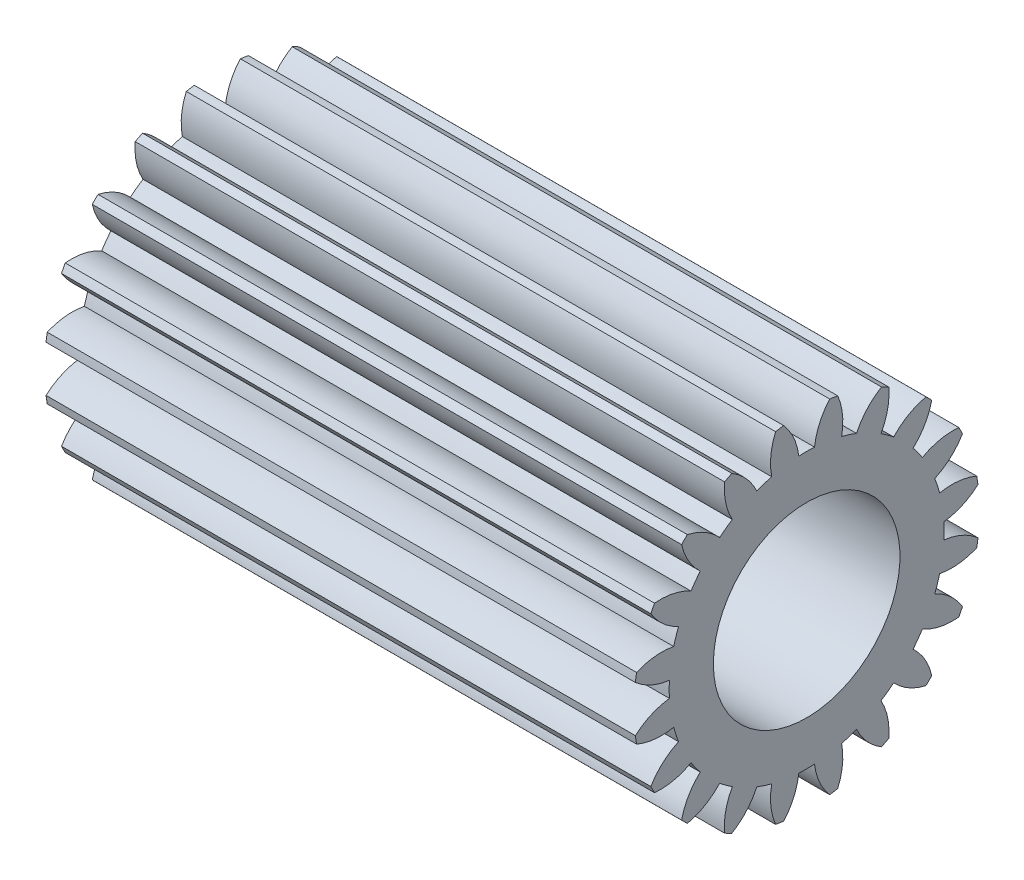
SolidWorks part; units mm, degrees
ref_plane "Plane1" through (0, 0, 0) normal (0, 0, 1) x (1, 0, 0)
ref_plane "Plane2" through (0, 0, 0) normal (0, 1, 0) x (1, 0, 0)
ref_plane "Plane3" through (0, 0, 0) normal (1, 0, 0) x (0, 0, -1)
sketch "HoldingSke" plane through (0, 0, 0) normal (0, 1, 0) x (1, 0, 0)
  line L0 (0, 0) -> (2.3492, -0.8551)
  line L1 (-15, 0) -> (100, 0) construction
  line L2 (0, 0) -> (-2.1039, 2.3779)
  line L3 (0, 0) -> (-11.863, 4.5341)
  line L4 (0, 0) -> (8.1152, 2.9537)
  line L5 (0, 0) -> (-46.8476, -17.4728)
  line L6 (0, 0) -> (-12.4344, -8.3896)
  line L7 (-2.1039, 2.3779) -> (8.6586, 51.2059)
  line L8 (-76.2, 54.61) -> (-75.9, 54.61)
  line L9 (-71.009, 38.7566) -> (-53.1078, 45.2721)
  line L10 (-76.2, 71.12) -> (104.1128, 71.12)
  line L11 (0, 0) -> (-15, 0)
  line L12 (-76.2, 101.6) -> (-76.185, 101.6)
  line L13 (24.9733, 27.94) -> (52.9518, 28.4284)
  line L14 (24.9733, 27.94) -> (24.9743, 27.94)
  line L15 (24.9733, 27.94) -> (100.4006, 29.5858)
  line L16 (-63.627, -0.4) -> (-12.827, -0.4)
  circle A0 centre (0, 0) radius 1
  circle A1 centre (0, 0) radius 3.499
  circle A2 centre (0, 0) radius 37.5
  circle A3 centre (0, 0) radius 2.375
  dimension "MHD" = 6.998
  dimension "Hub_dia" = 75
  dimension "Bore" = 2
  dimension "MBD" = 4.75
  dimension "Num_teeth" = 20
  dimension "Pitch" = 2.5
  dimension "Overall_len" = 50
  dimension "Show_teeth" = 20
  dimension "Thickness" = 15
  dimension "OAL" = 50.0001
  dimension "T_dim" = 0.3
  dimension "Ap" = 20
  dimension "H" = 19.05
  dimension "Pitch_radius" = 180.3128
  dimension "Width" = 15
  dimension "Backlash" = 0.015
  dimension "Addendum_fac" = 1
  dimension "Dedendum_fac" = 1.25
  dimension "Clearance_fac" = 0.25
  dimension "Dedendum_add" = 0.001
  dimension "Module" = 0.4
sketch "BasProSke" plane through (0, 0, 0) normal (0, 1, 0) x (1, 0, 0)
  line L0 (-10, 0) -> (60, 0) construction
  line L1 (0, 0) -> (0, 4.4)
  line L2 (0, 0) -> (15, 0)
  line L3 (15, 0) -> (15, 4.4)
  line L4 (15, 4.4) -> (0, 4.4)
  dimension "Thickness" = 15
  dimension "Diameter" = 8.8
revolve "Base-Revolve" add sketch "BasProSke" angle 360 about L0
sketch "TooCutSke" plane through (0, 0, 0) normal (1, 0, 0) x (0, 0, -1)
  line L1 (0, 0) -> (0, 107) construction
  line L2 (0, 0) -> (-0.3401, 3.9855) construction
  line L3 (0, 0) -> (-1.2482, 7.8811) construction
  line L4 (-0.3401, 3.9855) -> (-0.6241, 3.9405) construction
  arc A0 (0.1996, 3.4933) -> (-0.1996, 3.4933) centre (0, 0) ccw
  arc A1 (0.606, 4.3837) -> (-0.606, 4.3837) centre (0, 0) ccw
  circle A2 centre (0, 0) radius 4 construction
  circle A3 centre (0, 0) radius 3.7588 construction
  arc A4 (-0.1996, 3.4933) -> (-0.606, 4.3837) centre (-1.7886, 3.306) ccw
  arc A5 (0.606, 4.3837) -> (0.1996, 3.4933) centre (1.7886, 3.306) ccw
  dimension "Root_dia" = 6.998
  dimension "Overcut_dia" = 8.8508
  dimension "Pitch_dia" = 8
  dimension "Base_dia" = 7.5175
  dimension "Flank_rad" = 1.6
  dimension "Half_ang" = 9
  dimension "Half_CT" = 0.2876
extrude "ToothCut" cut sketch "TooCutSke" along normal through all
fillet "Breaks" [suppressed] radius 0.008
fillet "RootFillets" [suppressed] radius 0.101
pattern_circular "TeethCuts" count 20 every 18 about axis through (-10, 0, 0) along (1, 0, 0) of "ToothCut", "RootFillets", "Breaks"
sketch "HubNeaOneSke" plane through (0, 0, 0) normal (-1, 0, 0) x (0, 0, 1)
  circle A0 centre (0, 0) radius 3.499
  dimension "Diameter" = 6.998
extrude "HubNearOne" [suppressed] add sketch "HubNeaOneSke" along normal blind 35.0001
sketch "HubNeaBotSke" plane through (0, 0, 0) normal (-1, 0, 0) x (0, 0, 1)
  circle A0 centre (0, 0) radius 3.499
  dimension "Diameter" = 6.998
extrude "HubNearBoth" [suppressed] add sketch "HubNeaBotSke" along normal blind 17.5
ref_plane "FarPln" through (15, 0, 0) normal (1, 0, 0) x (0, 0, -1)
sketch "HubFarSke" plane through (15, 0, 0) normal (1, 0, 0) x (0, 0, -1)
  circle A0 centre (0, 0) radius 3.499
  dimension "Diameter" = 6.998
extrude "HubFar" [suppressed] add sketch "HubFarSke" along normal blind 17.5
sketch "BorSke" plane through (0, 0, 0) normal (1, 0, 0) x (0, 0, -1)
  circle A0 centre (0, 0) radius 2.375
  dimension "Diameter" = 4.75
extrude "Bore" cut sketch "BorSke" along normal mid plane 100.0001
sketch "KeySke" plane through (0, 0, 0) normal (1, 0, 0) x (0, 0, -1)
  line L0 (-0.4, 0) -> (-0.4, 2.675)
  line L1 (-0.4, 2.675) -> (0.4, 2.675)
  line L2 (0.4, 2.675) -> (0.4, 0)
  line L3 (0, 0) -> (0, 34) construction
  line L4 (-0.4, 0) -> (0.4, 0)
  dimension "Offset" = 2.675
  dimension "Width" = 0.8
extrude "Keyway" [suppressed] cut sketch "KeySke" along normal mid plane 100.0001
pattern_circular "Keyway2" [suppressed] count 2 every 90 about axis through (-10, 0, 0) along (1, 0, 0)
equation "' \"Module@HoldingSke\" = 6.35"
equation "' \"Num_teeth@HoldingSke\" = 12"
equation "' \"Ap@HoldingSke\" =  20"
equation "' \"Ap@HoldingSke\" = 20"
equation "' \"Width@HoldingSke\" = 0.5 * 25.4"
equation "' \"Hub_dia@HoldingSke\"= 1 * 25.4"
equation "' \"Hub_dia@HoldingSke\" = 1 * 25.4"
equation "' \"Overall_len@HoldingSke\" = 1.0 * 25.4"
equation "' \"Bore@HoldingSke\" = 0.75 * 25.4"
equation "' \"T_dim@HoldingSke\" = 0.1 * 25.4"
equation "' \"Width@KeySke\" = 0.25 * 25.4"
equation "' \"Show_teeth@HoldingSke\" = 13"
equation "' \"Backlash@HoldingSke\" = 0.009 * 25.4"
equation "' \"Addendum_fac@HoldingSke\" = 1.0"
equation "' \"Dedendum_fac@HoldingSke\" = 1.25"
equation "' \"Dedendum_add@HoldingSke\" = 0.00005 * 25.4"
equation "' \"Clearance_fac@HoldingSke\" = 0.25"
equation "\"Pitch@HoldingSke\" = 1 / \"Module@HoldingSke\""
equation "\"Overcut_dia@TooCutSke\" = (\"Num_teeth@HoldingSke\" + 2 * \"Addendum_fac@HoldingSke\") / \"Pitch@HoldingSke\" + 0.002 * 25.4"
equation "\"Pitch_dia@TooCutSke\" = \"Num_teeth@HoldingSke\" / \"Pitch@HoldingSke\""
equation "\"Base_dia@TooCutSke\" = \"Num_teeth@HoldingSke\" / \"Pitch@HoldingSke\" * cos((\"Ap@HoldingSke\"  * 3.14159265 / 180))"
equation "\"Root_dia@TooCutSke\" = (\"Num_teeth@HoldingSke\" + 2) / \"Pitch@HoldingSke\" - 2 * (\"Addendum_fac@HoldingSke\" + \"Dedendum_fac@HoldingSke\") / \"Pitch@HoldingSke\" - \"Dedendum_add@HoldingSke\" * 2"
equation "\"Half_ang@TooCutSke\" = 180 / \"Num_teeth@HoldingSke\""
equation "\"Half_CT@TooCutSke\" = \"Num_teeth@HoldingSke\" / \"Pitch@HoldingSke\" * sin((3.14159265 / 2 / \"Num_teeth@HoldingSke\")) / 2 - 7 * \"Backlash@HoldingSke\" / 4"
equation "\"Flank_rad@TooCutSke\" = \"Num_teeth@HoldingSke\" / \"Pitch@HoldingSke\" / 5"
equation "\"Radius@RootFillets\" = \"Clearance_fac@HoldingSke\" / \"Pitch@HoldingSke\" + \"Dedendum_add@HoldingSke\""
equation "\"Break_rad@Breaks\" = 0.02 / \"Pitch@HoldingSke\""
equation "\"Thickness@HoldingSke\" = \"Width@HoldingSke\""
equation "\"OAL@HoldingSke\" = \"Thickness@HoldingSke\""
equation "\"MHD@HoldingSke\" = (\"Num_teeth@HoldingSke\" + 2) / \"Pitch@HoldingSke\" - 2 * (\"Addendum_fac@HoldingSke\" + \"Dedendum_fac@HoldingSke\")  / \"Pitch@HoldingSke\" - \"Dedendum_add@HoldingSke\" * 2"
equation "\"MHD@HoldingSke\" = ((sgn( \"MHD@HoldingSke\" - \"Hub_dia@HoldingSke\" )-1)*( \"MHD@HoldingSke\" - \"Hub_dia@HoldingSke\" ))/-2+ \"Hub_dia@HoldingSke\""
equation "\"OAL@HoldingSke\" = ((sgn( \"OAL@HoldingSke\" - \"Overall_len@HoldingSke\" )+1)*( \"OAL@HoldingSke\" - \"Overall_len@HoldingSke\" ))/2 + \"Overall_len@HoldingSke\" + 0.000002 * 25.4"
equation "\"Num_teeth@TeethCuts\" = int( \"Show_teeth@HoldingSke\" ) + 1"
equation "\"Num_teeth@TeethCuts\" = ((sgn( \"Num_teeth@TeethCuts\" - \"Num_teeth@HoldingSke\" )-1)*( \"Num_teeth@TeethCuts\" - \"Num_teeth@HoldingSke\" ))/-2+ \"Num_teeth@HoldingSke\""
equation "\"Num_teeth@TeethCuts\" = ((sgn( \"Num_teeth@TeethCuts\" - 2.0)+1)*( \"Num_teeth@TeethCuts\" - 2.0))/2 +2.0"
equation "\"Angle@TeethCuts\" = 360.0 / \"Num_teeth@HoldingSke\""
equation "\"Diameter@BasProSke\" = (\"Num_teeth@HoldingSke\" + 2 * \"Addendum_fac@HoldingSke\") / \"Pitch@HoldingSke\""
equation "\"Thickness@BasProSke\"  = \"Thickness@HoldingSke\""
equation "' \"Fillet_rad@BasProSke\" =  \"Thickness@HoldingSke\" * 0.05"
equation "' \"Fillet_rad@BasProSke\" = \"Thickness@HoldingSke\" * 0.05"
equation "\"MHD@HoldingSke\" = ((sgn( \"MHD@HoldingSke\" - \"Root_dia@TooCutSke\" )-1)*( \"MHD@HoldingSke\" - \"Root_dia@TooCutSke\" ))/-2+ \"Root_dia@TooCutSke\""
equation "\"Diameter@HubNeaOneSke\" = \"MHD@HoldingSke\""
equation "\"Length@HubNearOne\" = \"OAL@HoldingSke\" - \"Thickness@BasProSke\""
equation "\"Diameter@HubNeaBotSke\" = \"MHD@HoldingSke\""
equation "\"Length@HubNearBoth\" = ( \"OAL@HoldingSke\" - \"Thickness@BasProSke\" ) / 2.0"
equation "\"Thickness@FarPln\" = \"Thickness@BasProSke\""
equation "\"Diameter@HubFarSke\" = \"MHD@HoldingSke\""
equation "\"Length@HubFar\" = ( \"OAL@HoldingSke\" - \"Thickness@BasProSke\" ) / 2.0"
equation "\"Diameter@BorSke\" = \"MBD@HoldingSke\""
equation "\"D1@Bore\" = \"OAL@HoldingSke\" * 2.0"
equation "\"D1@Keyway\" = \"OAL@HoldingSke\" * 2.0"
equation "\"Offset@KeySke\" = \"T_dim@HoldingSke\" + \"MBD@HoldingSke\" / 2.0"
